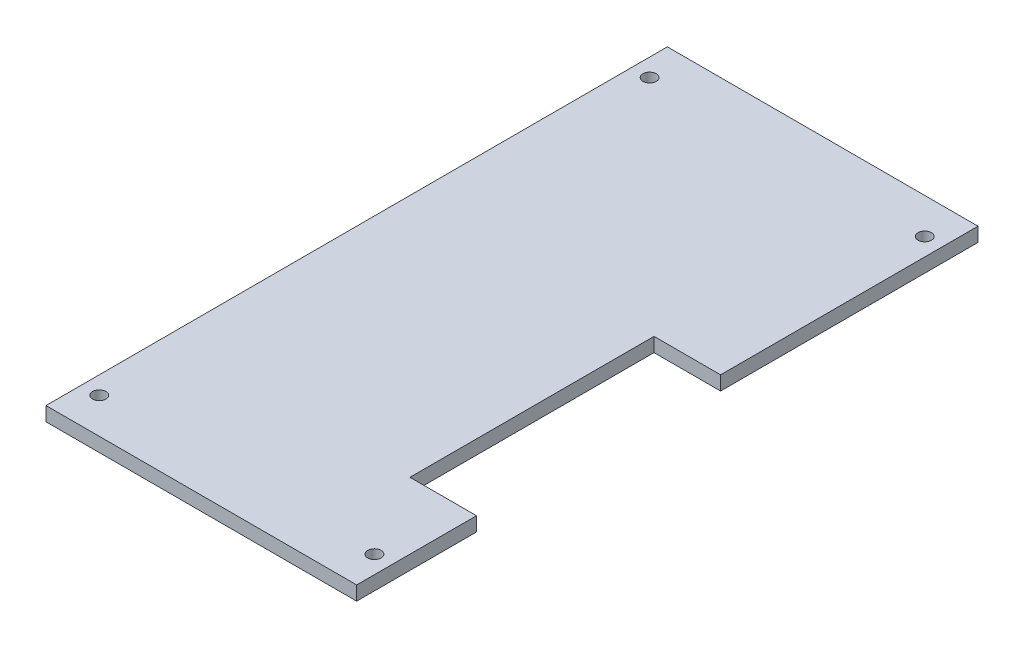
SolidWorks part; units mm, degrees
ref_plane "Front Plane" through (0, 0, 0) normal (0, 0, 1) x (1, 0, 0)
ref_plane "Top Plane" through (0, 0, 0) normal (0, 1, 0) x (1, 0, 0)
ref_plane "Right Plane" through (0, 0, 0) normal (1, 0, 0) x (0, 0, -1)
sketch "Sketch1" plane through (0, 0, 0) normal (0, 1, 0) x (1, 0, 0)
  line L0 (35, 12) -> (20, 12)
  line L1 (35, -70) -> (-35, -70)
  line L2 (35, -70) -> (35, -43)
  line L3 (35, 70) -> (-35, 70)
  line L4 (-35, -70) -> (-35, 70)
  line L5 (35, -70) -> (-35, 70) construction
  line L6 (35, 70) -> (-35, -70) construction
  line L7 (20, 12) -> (20, -43)
  line L8 (20, -43) -> (35, -43)
  line L9 (0, -70) -> (0, 70) construction
  line L10 (-35, 0) -> (35, 0) construction
  line L11 (35, 12) -> (35, 70)
  circle A0 centre (31, -62) radius 1.5
  circle A1 centre (-31, -62) radius 1.5
  circle A2 centre (-31, 62) radius 1.5
  circle A3 centre (31, 62) radius 1.5
  point P0 (0, 0)
  dimension "D6" = 4
  dimension "D1" = 70
  dimension "D2" = 140
  dimension "D3" = 15
  dimension "D4" = 55
  dimension "D5" = 27
  dimension "D7" = 8
extrude "Boss-Extrude1" add sketch "Sketch1" along normal blind 3.175
